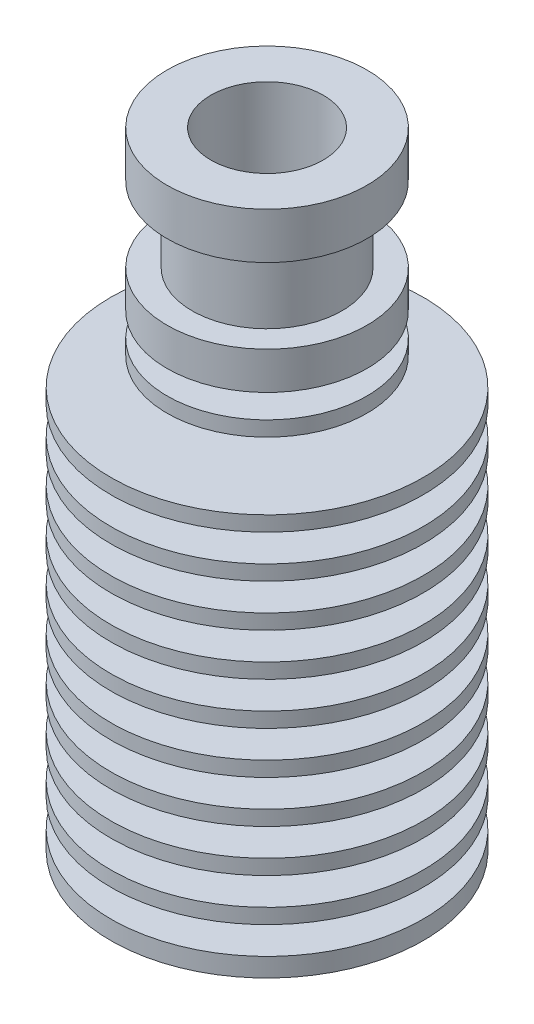
SolidWorks part; units mm, degrees
material "3.1255 (EN-AW 2014)"
ref_plane "Přední rovina" through (0, 0, 0) normal (0, 0, 1) x (1, 0, 0)
ref_plane "Horní rovina" through (0, 0, 0) normal (0, 1, 0) x (1, 0, 0)
ref_plane "Pravá rovina" through (0, 0, 0) normal (1, 0, 0) x (0, 0, -1)
sketch "Skica1" plane through (0, 0, 0) normal (0, 0, 1) x (1, 0, 0)
  line L0 (0, 64.6375) -> (0, 60.9375) construction
  line L1 (0, 60.9375) -> (0, 54.9375) construction
  line L2 (0, 54.9375) -> (0, 51.9375) construction
  line L3 (0, 64.6375) -> (8, 64.6375) construction
  line L4 (0, 60.9375) -> (6, 60.9375) construction
  line L5 (0, 54.9375) -> (6, 54.9375) construction
  line L6 (0, 51.9375) -> (8, 51.9375) construction
  line L7 (8, 64.6375) -> (4.5, 64.6375)
  line L8 (8, 64.6375) -> (8, 60.9375)
  line L9 (8, 60.9375) -> (6, 60.9375)
  line L10 (6, 60.9375) -> (6, 54.9375)
  line L11 (8, 54.9375) -> (6, 54.9375)
  line L12 (8, 54.9375) -> (8, 51.9375)
  line L13 (0, 51.9375) -> (4.5, 51.9375) construction
  line L14 (8, 51.9375) -> (4.5, 51.9375)
  line L15 (0, 64.6375) -> (0, 50.0375) construction
  line L16 (0, 64.6375) -> (0, 46.6375) construction
  line L17 (0, 64.6375) -> (0, 14.5375) construction
  line L18 (0, 50.0375) -> (0, 36.4375) construction
  line L19 (0, 36.4375) -> (0, 33.0375) construction
  line L20 (0, 50.0375) -> (8, 50.0375) construction
  line L21 (4, 50.0375) -> (4, 48.8375) construction
  line L22 (4.5, 51.9375) -> (4.5, 50.0375)
  line L23 (4.5, 50.0375) -> (8, 50.0375)
  line L24 (8, 50.0375) -> (8, 48.8375)
  line L25 (8, 48.8375) -> (4, 48.8375)
  line L26 (4, 48.8375) -> (4, 46.6375)
  line L27 (0, 46.6375) -> (12.5, 46.6375) construction
  line L28 (4, 46.6375) -> (12.5, 46.6375)
  line L29 (12.5, 46.6375) -> (12.5, 45.4375)
  line L30 (12.5, 45.4375) -> (4, 45.4375)
  line L31 (4, 45.4375) -> (4, 43.2375)
  line L32 (4, 43.2375) -> (12.5, 43.2375)
  line L33 (12.5, 43.2375) -> (12.5, 42.0375)
  line L34 (12.5, 42.0375) -> (4, 42.0375)
  line L35 (4, 42.0375) -> (4, 39.8375)
  line L36 (4, 39.8375) -> (12.5, 39.8375)
  line L37 (12.5, 39.8375) -> (12.5, 38.6375)
  line L38 (12.5, 38.6375) -> (4, 38.6375)
  line L39 (4, 38.6375) -> (4, 36.4375)
  line L40 (4, 36.4375) -> (12.5, 36.4375)
  line L41 (12.5, 36.4375) -> (12.5, 35.2375)
  line L42 (0, 35.2375) -> (6.5, 35.2375) construction
  line L43 (12.5, 35.2375) -> (6.5, 35.2375)
  line L44 (6.5, 35.2375) -> (6.5, 33.0375)
  line L45 (6.5, 33.0375) -> (12.5, 33.0375)
  line L46 (12.5, 33.0375) -> (12.5, 31.8375)
  line L47 (0, 31.8375) -> (7.5, 31.8375) construction
  line L48 (12.5, 31.8375) -> (7.5, 31.8375)
  line L49 (7.5, 31.8375) -> (7.5, 29.6375)
  line L50 (7.5, 29.6375) -> (12.5, 29.6375)
  line L51 (12.5, 29.6375) -> (12.5, 28.4375)
  line L52 (12.5, 28.4375) -> (7.5, 28.4375)
  line L53 (7.5, 28.4375) -> (7.5, 26.2375)
  line L54 (7.5, 26.2375) -> (12.5, 26.2375)
  line L55 (12.5, 26.2375) -> (12.5, 25.0375)
  line L56 (12.5, 25.0375) -> (7.5, 25.0375)
  line L57 (7.5, 25.0375) -> (7.5, 22.8375)
  line L58 (7.5, 22.8375) -> (12.5, 22.8375)
  line L59 (12.5, 22.8375) -> (12.5, 21.6375)
  line L60 (12.5, 21.6375) -> (7.5, 21.6375)
  line L61 (7.5, 21.6375) -> (7.5, 19.4375)
  line L62 (7.5, 19.4375) -> (12.5, 19.4375)
  line L63 (12.5, 19.4375) -> (12.5, 18.2375)
  line L64 (12.5, 18.2375) -> (7.5, 18.2375)
  line L65 (7.5, 18.2375) -> (7.5, 16.0375)
  line L66 (7.5, 16.0375) -> (12.5, 16.0375)
  line L67 (12.5, 16.0375) -> (12.5, 14.5375)
  line L68 (3, 14.5375) -> (12.5, 14.5375)
  line L69 (0, 14.5375) -> (3, 14.5375) construction
  line L70 (3, 14.5375) -> (3, 31.8375)
  line L71 (0, 36.4375) -> (1, 36.4375) construction
  line L72 (2, 46.9362) -> (2, 31.8375)
  line L73 (2, 31.8375) -> (3, 31.8375)
  line L74 (0, 46.6375) -> (0, 50.6375) construction
  line L75 (0, 50.6375) -> (2, 50.6375) construction
  line L76 (2, 50.6375) -> (2, 46.9362)
  line L78 (2, 50.6375) -> (4.5, 52.9746)
  line L79 (4.5, 52.9746) -> (4.5, 64.6375)
  dimension "D1" = 3.7
  dimension "D2" = 6
  dimension "D3" = 3
  dimension "D4" = 12.7
  dimension "D5" = 8
  dimension "D6" = 6
  dimension "D7" = 4.5
  dimension "D8" = 14.6
  dimension "D9" = 18
  dimension "D10" = 50.1
  dimension "D11" = 13.6
  dimension "D12" = 3.4
  dimension "D13" = 18.5
  dimension "D14" = 8
  dimension "D15" = 1.2
  dimension "D16" = 2.2
  dimension "D17" = 12.5
  dimension "D18" = 6.5
  dimension "D19" = 7.5
  dimension "D20" = 5
  dimension "D21" = 1
  dimension "D22" = 3
  dimension "D23" = 17.3
  dimension "D25" = 4
  dimension "D26" = 2
  dimension "D28" = 11.6629
  dimension "D29" = 3.4223
revolve "Rotovat1" add sketch "Skica1" angle 360 about L17
